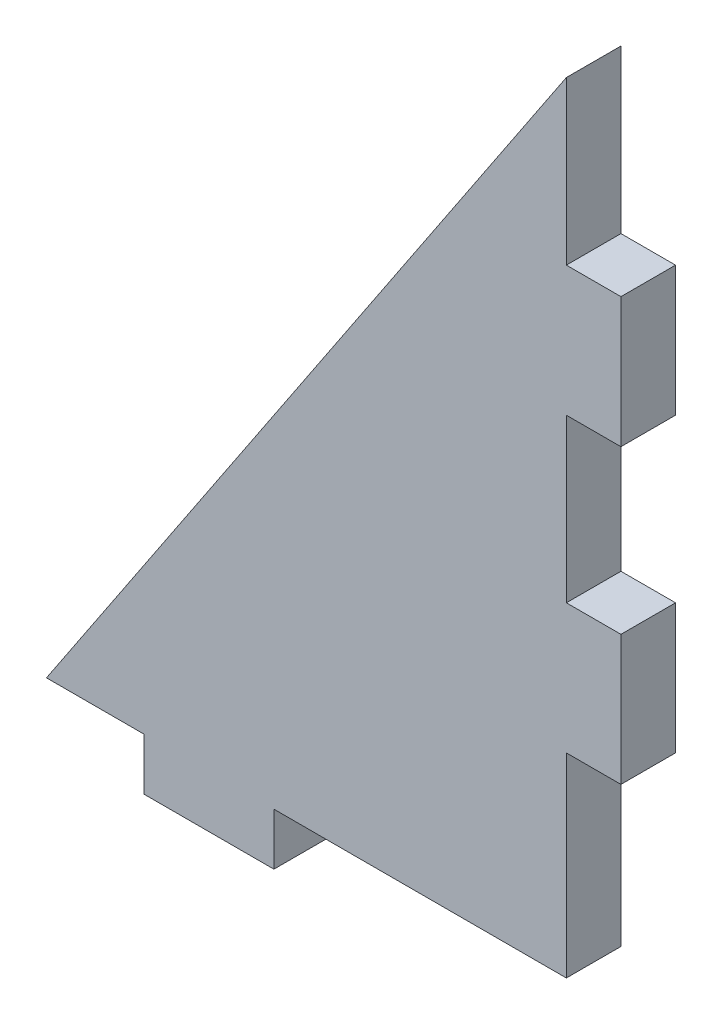
SolidWorks part; units mm, degrees
ref_plane "Front" through (0, 0, 0) normal (0, 0, 1) x (1, 0, 0)
ref_plane "Top" through (0, 0, 0) normal (0, 1, 0) x (1, 0, 0)
ref_plane "Right" through (0, 0, 0) normal (1, 0, 0) x (0, 0, -1)
sketch "Sketch1" plane through (0, 0, 0) normal (0, 0, 1) x (1, 0, 0)
  line L0 (0, 0) -> (0, 19.05)
  line L1 (0, 76.2) -> (-50.8, 0)
  line L2 (-28.575, 0) -> (0, 0)
  line L4 (-41.275, -5.08) -> (-28.575, -5.08)
  line L5 (-28.575, -5.08) -> (-28.575, 0)
  line L6 (0, 19.05) -> (5.334, 19.05)
  line L7 (5.334, 19.05) -> (5.334, 31.75)
  line L8 (5.334, 31.75) -> (0, 31.75)
  line L10 (5.334, 60.325) -> (5.334, 47.625)
  line L11 (5.334, 47.625) -> (0, 47.625)
  line L12 (0, 31.75) -> (0, 47.625)
  line L13 (0, 76.2) -> (0, 60.325)
  line L14 (0, 60.325) -> (5.334, 60.325)
  line L15 (-50.8, 0) -> (-41.275, 0)
  line L16 (-41.275, 0) -> (-41.275, -5.08)
  point P16 (5.334, 25.4)
  point P17 (5.334, 53.975)
  dimension "D1" = 76.2
  dimension "D2" = 50.8
  dimension "D3" = 12.7
  dimension "D4" = 5.08
  dimension "D5" = 28.575
  dimension "D6" = 56.31
  dimension "D7" = 19.05
  dimension "D8" = 9.525
  dimension "D9" = 5.334
extrude "Boss-Extrude1" add sketch "Sketch1" along normal blind 5.334
